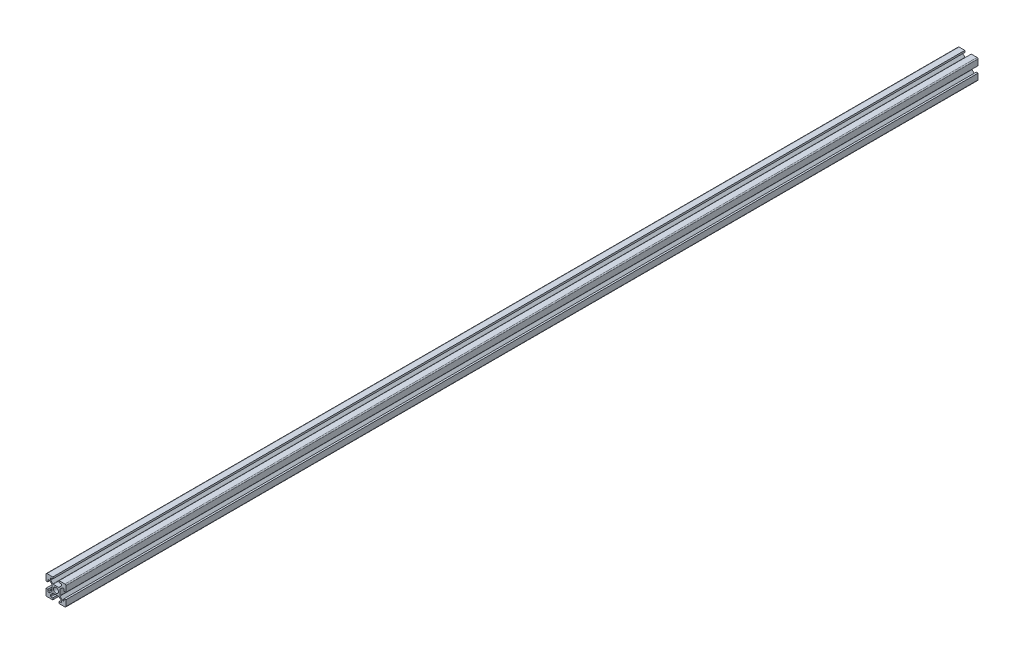
SolidWorks part; units mm, degrees
material "1060 Alloy"
ref_plane "Front Plane" through (0, 0, 0) normal (0, 0, 1) x (1, 0, 0)
ref_plane "Top Plane" through (0, 0, 0) normal (0, 1, 0) x (1, 0, 0)
ref_plane "Right Plane" through (0, 0, 0) normal (1, 0, 0) x (0, 0, -1)
sketch "Sketch1" plane through (0, 0, 0) normal (0, 0, 1) x (1, 0, 0)
  line L0 (20, 0) -> (-8.059, 28.059) construction
  line L1 (0, 0) -> (6.8, 0)
  line L2 (0, 0) -> (0, 6.8)
  line L3 (0, 20) -> (6.8, 20)
  line L4 (20, 0) -> (20, 6.8)
  line L5 (6.8, 20) -> (6.8, 18.2)
  line L6 (20, 20) -> (8.2322, 8.2322) construction
  line L7 (12.95, 6.1) -> (7.05, 6.1)
  line L8 (13.9, 7.05) -> (13.9, 12.95)
  line L9 (12.95, 13.9) -> (7.05, 13.9)
  line L10 (6.1, 7.05) -> (6.1, 12.95)
  line L11 (13.9, 6.1) -> (6.1, 13.9) construction
  line L12 (13.9, 13.9) -> (6.1, 6.1) construction
  line L13 (4.55, 16.4) -> (7.05, 13.9)
  line L14 (13.2, 18.2) -> (13.2, 20)
  line L15 (1.8, 6.8) -> (0, 6.8)
  line L16 (0, 13.2) -> (0, 20)
  line L17 (0, 13.2) -> (1.8, 13.2)
  line L18 (10, 10) -> (10, 13.9) construction
  line L19 (16.4, 4.55) -> (13.9, 7.05)
  line L20 (4.55, 16.4) -> (4.55, 18.2)
  line L21 (4.55, 18.2) -> (6.8, 18.2)
  line L22 (13.2, 18.2) -> (15.45, 18.2)
  line L23 (15.45, 18.2) -> (15.45, 16.4)
  line L24 (15.45, 16.4) -> (12.95, 13.9)
  line L25 (16.4, 4.55) -> (18.2, 4.55)
  line L26 (18.2, 4.55) -> (18.2, 6.8)
  line L27 (20, 6.8) -> (18.2, 6.8)
  line L28 (18.2, 13.2) -> (20, 13.2)
  line L29 (18.2, 13.2) -> (18.2, 15.45)
  line L30 (18.2, 15.45) -> (16.4, 15.45)
  line L31 (16.4, 15.45) -> (13.9, 12.95)
  line L32 (1.8, 4.55) -> (3.6, 4.55)
  line L33 (3.6, 15.45) -> (6.1, 12.95)
  line L34 (3.6, 15.45) -> (1.8, 15.45)
  line L35 (1.8, 15.45) -> (1.8, 13.2)
  line L36 (0, 13.2) -> (1.8, 13.2)
  line L37 (1.8, 6.8) -> (0, 6.8)
  line L38 (3.6, 4.55) -> (6.1, 7.05)
  line L39 (1.8, 6.8) -> (1.8, 4.55)
  line L40 (15.45, 3.6) -> (12.95, 6.1)
  line L41 (4.55, 3.6) -> (7.05, 6.1)
  line L42 (4.55, 1.8) -> (4.55, 3.6)
  line L43 (6.8, 1.8) -> (4.55, 1.8)
  line L44 (6.8, 1.8) -> (6.8, 0)
  line L45 (15.45, 3.6) -> (15.45, 1.8)
  line L46 (15.45, 1.8) -> (13.2, 1.8)
  line L47 (13.2, 0) -> (13.2, 1.8)
  line L48 (13.2, 20) -> (20, 20)
  line L49 (20, 13.2) -> (20, 20)
  line L50 (13.2, 0) -> (20, 0)
  line L51 (6.1, 6.1) -> (-5.5045, -5.5045) construction
  circle A0 centre (10, 10) radius 2.5
  point P25 (10, 16.4)
  point P39 (13.2, 19.1)
  point P46 (0.9, 6.8)
  dimension "D3" = 5
  dimension "D2" = 20
  dimension "D4" = 7.8
  dimension "D5" = 7.8
  dimension "D6" = 6.8
  dimension "D7" = 6.8
  dimension "D8" = 1.8
  dimension "D9" = 10.9
  dimension "D10" = 1.8
  dimension "D11" = 10.9
  dimension "D12" = 20
extrude "Boss-Extrude1" add sketch "Sketch1" along normal blind 915 contours L47 L50 L4 L27 L26 L25 L19 L8 L31 L30 L29 L28 L49 L48 L14 L22 L23 L24 L9 L13 L20 L21 L5 L3 L16 L17 L35 L34 L33 L10 L38 L32 L39 L15 L2 L1 L44 L43 L42 L41 L7 L40 L45 L46 A0
fillet "Fillet1" radius 1 4 edges at (20, 20, 457.5) (20, 0, 457.5) (0, 0, 457.5) (0, 20, 457.5)
fillet "Fillet2" radius 0.5 6 edges at (4.55, 18.2, 457.5) (4.55, 16.4, 457.5) (7.05, 13.9, 457.5) (15.45, 18.2, 457.5) (15.45, 16.4, 457.5) (12.95, 13.9, 457.5)
fillet "Fillet3" radius 0.5 6 edges at (18.2, 15.45, 457.5) (16.4, 15.45, 457.5) (13.9, 12.95, 457.5) (18.2, 4.55, 457.5) (13.9, 7.05, 457.5) (16.4, 4.55, 457.5)
fillet "Fillet4" radius 0.5 6 edges at (1.8, 15.45, 457.5) (3.6, 15.45, 457.5) (6.1, 12.95, 457.5) (3.6, 4.55, 457.5) (1.8, 4.55, 457.5) (6.1, 7.05, 457.5)
fillet "Fillet5" radius 0.5 6 edges at (7.05, 6.1, 457.5) (4.55, 3.6, 457.5) (4.55, 1.8, 457.5) (15.45, 1.8, 457.5) (15.45, 3.6, 457.5) (12.95, 6.1, 457.5)
